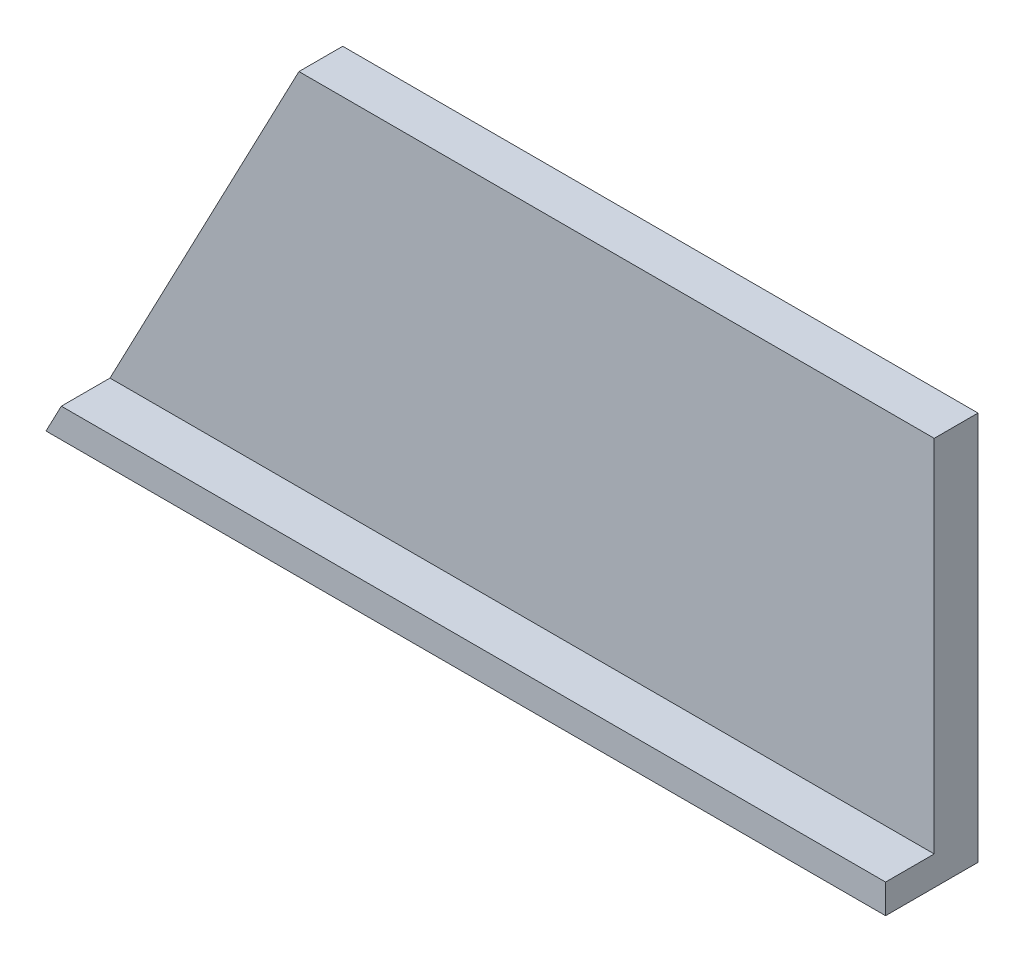
SolidWorks part; units mm, degrees
ref_plane "前视基准面" through (0, 0, 0) normal (0, 0, 1) x (1, 0, 0)
ref_plane "上视基准面" through (0, 0, 0) normal (0, 1, 0) x (1, 0, 0)
ref_plane "右视基准面" through (0, 0, 0) normal (1, 0, 0) x (0, 0, -1)
sketch "草图1" plane through (0, 0, 0) normal (0, 1, 0) x (1, 0, 0)
  line L1 (0, 0) -> (135.4, 0)
  line L2 (0, 0) -> (0, -96.8)
  line L3 (0, -96.8) -> (135.4, -96.8)
  line L4 (135.4, 0) -> (135.4, -96.8)
  line L5 (9.5, -21.9) -> (35.5, -21.9)
  line L6 (5, -26.4) -> (5, -70.4)
  line L7 (9.5, -74.9) -> (35.5, -74.9)
  line L8 (40, -26.4) -> (40, -70.4)
  arc A0 (5, -70.4) -> (9.5, -74.9) centre (9.5, -70.4) ccw
  arc A1 (35.5, -74.9) -> (40, -70.4) centre (35.5, -70.4) ccw
  arc A2 (35.5, -21.9) -> (40, -26.4) centre (35.5, -26.4) cw
  arc A3 (9.5, -21.9) -> (5, -26.4) centre (9.5, -26.4) ccw
  point P9 (5, -48.4)
  point P10 (0, -48.4)
  dimension "D6" = 4.5
  dimension "D1" = 96.8
  dimension "D2" = 135.4
  dimension "D3" = 5
  dimension "D4" = 35
  dimension "D5" = 53
extrude "凸台-拉伸1" add sketch "草图1" along normal blind 4.5
sketch "草图2" plane through (0, 4.5, 0) normal (0, 1, 0) x (1, 0, 0)
  line L0 (135.4, -96.8) -> (135.4, 0) construction
  line L1 (0, 0) -> (135.4, 0)
  line L2 (0, 0) -> (0, -4.5)
  line L3 (0, -4.5) -> (135.4, -4.5)
  line L4 (135.4, 0) -> (135.4, -4.5)
  line L5 (0, 0) -> (0, -96.8) construction
  line L6 (0, -92.3) -> (135.4, -92.3)
  line L7 (0, -92.3) -> (0, -96.8)
  line L8 (0, -96.8) -> (135.4, -96.8)
  line L9 (135.4, -92.3) -> (135.4, -96.8)
  dimension "D1" = 4.5
  dimension "D2" = 4.5
extrude "凸台-拉伸2" add sketch "草图2" along normal blind 40
sketch "草图3" plane through (0, 0, 96.8) normal (0, 0, 1) x (1, 0, 0)
  line L0 (47.7, 44.5) -> (87.7, 44.5)
  line L1 (0, 44.5) -> (135.4, 44.5) construction
  arc A0 (87.7, 44.5) -> (47.7, 44.5) centre (67.7, 44.5) cw
  point P4 (67.7, 44.5)
  dimension "D1" = 20
extrude "切除-拉伸1" cut sketch "草图3" against normal blind 40
sketch "草图4" plane through (0, 0, 0) normal (-1, 0, 0) x (0, 0, 1)
  line L0 (96.8, 44.5) -> (96.8, 0) construction
  line L1 (0, 0) -> (96.8, 0)
  line L2 (0, 0) -> (0, 4.5)
  line L3 (0, 4.5) -> (96.8, 4.5)
  line L4 (96.8, 0) -> (96.8, 4.5)
  line L5 (4.5, 4.5) -> (92.3, 4.5) construction
extrude "凸台-拉伸3" add sketch "草图4" along normal blind 21
sketch "草图5" plane through (135.4, 0, 0) normal (1, 0, 0) x (0, 0, -1)
  line L0 (-96.8, 44.5) -> (-96.8, 0) construction
  line L1 (0, 0) -> (-96.8, 0)
  line L2 (0, 0) -> (0, 4.5)
  line L3 (0, 4.5) -> (-96.8, 4.5)
  line L4 (-96.8, 0) -> (-96.8, 4.5)
  line L5 (-92.3, 4.5) -> (-4.5, 4.5) construction
extrude "凸台-拉伸4" add sketch "草图5" along normal blind 21
sketch "草图6" plane through (0, 4.5, 0) normal (0, 1, 0) x (1, 0, 0)
  line L0 (0, -4.5) -> (135.4, -4.5) construction
  line L1 (-16.5, -4.5) -> (-14, -4.5)
  line L2 (-16.5, -4.5) -> (-16.5, -92.3)
  line L3 (-16.5, -92.3) -> (-14, -92.3)
  line L4 (-14, -4.5) -> (-14, -92.3)
  line L5 (149.4, -4.5) -> (151.9, -4.5)
  line L6 (149.4, -4.5) -> (149.4, -92.3)
  line L7 (149.4, -92.3) -> (151.9, -92.3)
  line L8 (151.9, -4.5) -> (151.9, -92.3)
  line L9 (135.4, -92.3) -> (0, -92.3) construction
  line L10 (135.4, -92.3) -> (0, -92.3) construction
  line L11 (-21, -96.8) -> (-21, 0) construction
  line L12 (156.4, 0) -> (156.4, -96.8) construction
  dimension "D1" = 4.5
  dimension "D2" = 4.5
  dimension "D3" = 2.5
  dimension "D4" = 2.5
extrude "切除-拉伸2" cut sketch "草图6" against normal through all
sketch "草图7" plane through (0, 4.5, 0) normal (0, 1, 0) x (1, 0, 0)
  line L1 (135.4, -4.5) -> (156.4, -4.5)
  line L2 (135.4, -4.5) -> (135.4, 0)
  line L3 (135.4, 0) -> (156.4, 0)
  line L4 (156.4, -4.5) -> (156.4, 0)
  line L5 (156.4, 0) -> (156.4, -96.8) construction
  line L6 (135.4, -96.8) -> (156.4, -96.8)
  line L7 (135.4, -96.8) -> (135.4, -92.3)
  line L8 (135.4, -92.3) -> (156.4, -92.3)
  line L9 (156.4, -96.8) -> (156.4, -92.3)
  line L10 (-21, -4.5) -> (0, -4.5)
  line L11 (-21, -4.5) -> (-21, 0)
  line L12 (-21, 0) -> (0, 0)
  line L13 (0, -4.5) -> (0, 0)
  line L14 (-21, -92.3) -> (0, -92.3)
  line L15 (-21, -92.3) -> (-21, -96.8)
  line L16 (-21, -96.8) -> (0, -96.8)
  line L17 (0, -92.3) -> (0, -96.8)
  line L18 (-21, -96.8) -> (0, -96.8) construction
  line L19 (156.4, 0) -> (135.4, 0) construction
extrude "凸台-拉伸6" add sketch "草图7" along normal blind 40
sketch "草图9" plane through (0, 0, 4.5) normal (0, 0, 1) x (1, 0, 0)
  line L0 (-14, 4.5) -> (149.4, 4.5) construction
  line L2 (70.1, 4.5) -> (65.3, 4.5)
  line L3 (70.1, 4.5) -> (70.1, 44.5)
  line L4 (70.1, 44.5) -> (65.3, 44.5)
  line L5 (65.3, 4.5) -> (65.3, 44.5)
  line L6 (7, 44.5) -> (135.4, 44.5) construction
  point P8 (67.7, 4.5)
  dimension "D1" = 4.8
extrude "切除-拉伸4" cut sketch "草图9" against normal through all
sketch "草图10" plane through (0, 0, 96.8) normal (0, 0, 1) x (1, 0, 0)
  line L0 (-21, 44.5) -> (0, 44.5)
  line L1 (-21, 44.5) -> (47.7, 44.5) construction
  line L2 (0, 44.5) -> (-21, 4.5)
  line L3 (-21, 4.5) -> (-21, 44.5)
  line L4 (156.4, 44.5) -> (156.4, 4.5)
  line L5 (156.4, 44.5) -> (156.4, 0) construction
  line L6 (156.4, 4.5) -> (135.4, 44.5)
  line L7 (87.7, 44.5) -> (156.4, 44.5) construction
  line L8 (135.4, 44.5) -> (156.4, 44.5)
  dimension "D1" = 21
  dimension "D2" = 21
extrude "切除-拉伸5" cut sketch "草图10" against normal through all
sketch "草图11" plane through (0, 4.5, 0) normal (0, 1, 0) x (1, 0, 0)
  line L0 (149.4, -4.5) -> (149.4, -92.3) construction
  line L1 (45, -23.4) -> (125, -23.4)
  line L2 (45, -23.4) -> (45, -73.4)
  line L3 (45, -73.4) -> (125, -73.4)
  line L4 (125, -23.4) -> (125, -73.4)
  line L5 (40, -70.4) -> (40, -26.4) construction
  point P4 (125, -48.4)
  point P5 (149.4, -48.4)
  dimension "D1" = 80
  dimension "D2" = 50
  dimension "D3" = 5
extrude "切除-拉伸6" cut sketch "草图11" against normal blind 0.3
sketch "草图12" plane through (0, 4.2, 0) normal (0, 1, 0) x (1, 0, 0)
  line L0 (125, -23.4) -> (45, -23.4) construction
  line L2 (125, -73.4) -> (125, -23.4) construction
  text T0 "<b> 请在此贴NFC芯片</b>" font "黑体" height in points 18
  dimension "D1" = 29.0049
  dimension "D2" = 77
extrude "凸台-拉伸9" add sketch "草图12" along normal blind 0.1
sketch "草图13" plane through (0, 0, 96.8) normal (0, 0, 1) x (1, 0, 0)
  line L1 (-21, 4.5) -> (156.4, 4.5)
  line L2 (-21, 4.5) -> (-21, 0)
  line L3 (-21, 0) -> (156.4, 0)
  line L4 (156.4, 4.5) -> (156.4, 0)
extrude "切除-拉伸7" cut sketch "草图13" against normal blind 100
sketch "草图14" plane through (0, 0, 4.5) normal (0, 0, 1) x (1, 0, 0)
  line L0 (0, 44.5) -> (135.4, 44.5)
  line L1 (135.4, 44.5) -> (156.4, 4.5)
  line L2 (156.4, 4.5) -> (-21, 4.5)
  line L3 (-21, 4.5) -> (0, 44.5)
extrude "切除-拉伸8" cut sketch "草图14" along normal blind 119
sketch "草图15" plane through (0, 0, 4.5) normal (0, 0, 1) x (1, 0, 0)
  line L0 (-21, 4.5) -> (156.4, 4.5)
  line L1 (156.4, 4.5) -> (154.825, 7.5)
  line L2 (156.4, 4.5) -> (135.4, 44.5) construction
  line L3 (154.825, 7.5) -> (-19.425, 7.5)
  line L4 (0, 44.5) -> (-21, 4.5) construction
  line L5 (-19.425, 7.5) -> (-21, 4.5)
  dimension "D1" = 3
extrude "凸台-拉伸10" add sketch "草图15" along normal blind 5
sketch "草图16" plane through (0, 0, 4.5) normal (0, 0, -1) x (-1, 0, 0)
  line L1 (-65.3, 7.5) -> (-70.1, 7.5)
  line L2 (-65.3, 7.5) -> (-65.3, 4.5)
  line L3 (-65.3, 4.5) -> (-70.1, 4.5)
  line L4 (-70.1, 7.5) -> (-70.1, 4.5)
extrude "切除-拉伸9" cut sketch "草图16" against normal blind 5
sketch "草图17" plane through (0, 0, 0) normal (0, 0, -1) x (-1, 0, 0)
  line L0 (-65.3, 44.5) -> (0, 44.5)
  line L1 (0, 44.5) -> (21, 4.5)
  line L2 (21, 4.5) -> (-65.3, 4.5)
  line L3 (-65.3, 4.5) -> (-65.3, 44.5)
extrude "切除-拉伸11" cut sketch "草图17" against normal blind 50 flip side to cut
